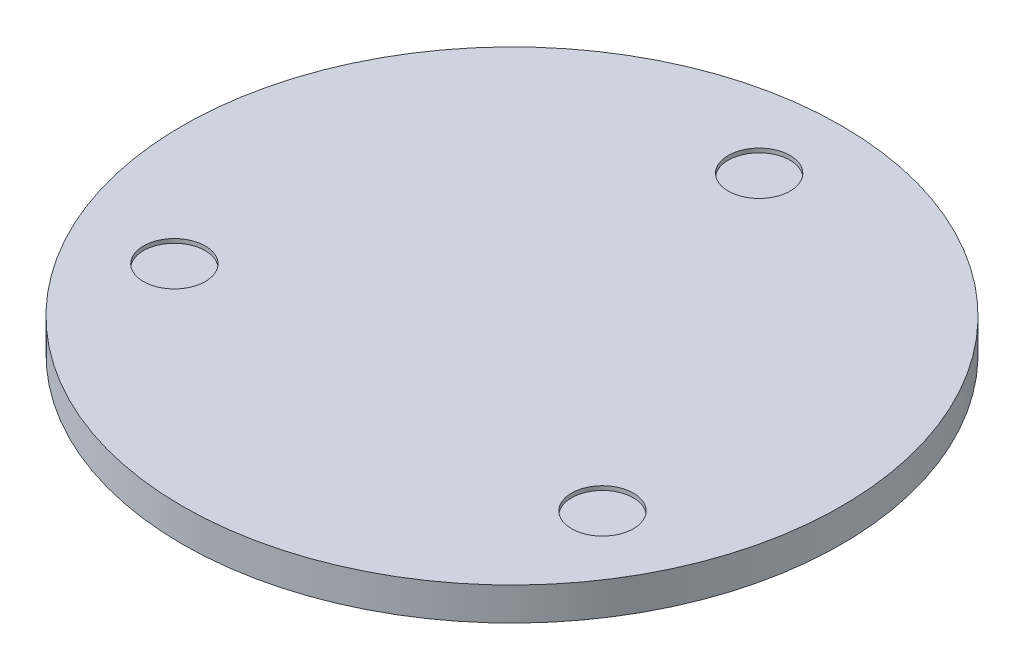
SolidWorks part; units mm, degrees
ref_plane "Front Plane" through (0, 0, 0) normal (0, 0, 1) x (1, 0, 0)
ref_plane "Top Plane" through (0, 0, 0) normal (0, 1, 0) x (1, 0, 0)
ref_plane "Right Plane" through (0, 0, 0) normal (1, 0, 0) x (0, 0, -1)
sketch "Sketch1" plane through (0, 0, 0) normal (0, 0, 1) x (1, 0, 0)
  line L0 (0, 0) -> (-50.8, 0)
  line L1 (-50.8, 0) -> (-50.8, -5.08)
  line L2 (-50.8, -5.08) -> (-38.1, -5.08)
  line L3 (-38.1, -5.08) -> (-38.1, -2.54)
  line L4 (-38.1, -2.54) -> (0, -2.54)
  line L5 (0, -2.54) -> (0, 0)
  dimension "D1" = 50.8
  dimension "D2" = 12.7
  dimension "D3" = 5.08
  dimension "D4" = 2.54
sketch "Sketch2" plane through (0, 0, 0) normal (0, 0, 1) x (1, 0, 0)
  line L0 (0, 4.5677) -> (0, -8.0056) construction
revolve "Revolve1" add sketch "Sketch1" angle 360 about L0
sketch "Sketch3" plane through (0, 0, 0) normal (0, 1, 0) x (1, 0, 0)
  line L0 (0, 0) -> (0, 38.1) construction
  line L1 (0, 0) -> (-32.9956, -19.05) construction
  line L2 (0, 0) -> (32.9956, -19.05) construction
  line L4 (-1.8331, 41.275) -> (-3.6662, 38.1)
  line L5 (-3.6662, 38.1) -> (-1.8331, 34.925)
  line L6 (-1.8331, 34.925) -> (1.8331, 34.925)
  line L7 (1.8331, 34.925) -> (3.6662, 38.1)
  line L8 (3.6662, 38.1) -> (1.8331, 41.275)
  line L9 (1.8331, 41.275) -> (-1.8331, 41.275)
  line L10 (-34.8287, -15.875) -> (-36.6617, -19.05)
  line L11 (-36.6617, -19.05) -> (-34.8287, -22.225)
  line L12 (-34.8287, -22.225) -> (-31.1625, -22.225)
  line L13 (-31.1625, -22.225) -> (-29.3294, -19.05)
  line L14 (-29.3294, -19.05) -> (-31.1625, -15.875)
  line L15 (-31.1625, -15.875) -> (-34.8287, -15.875)
  line L16 (34.8287, -15.875) -> (31.1625, -15.875)
  line L17 (31.1625, -15.875) -> (29.3294, -19.05)
  line L18 (29.3294, -19.05) -> (31.1625, -22.225)
  line L19 (31.1625, -22.225) -> (34.8287, -22.225)
  line L20 (34.8287, -22.225) -> (36.6617, -19.05)
  line L21 (36.6617, -19.05) -> (34.8287, -15.875)
  circle A0 centre (0, 38.1) radius 3.175 construction
  circle A1 centre (-32.9956, -19.05) radius 3.175 construction
  circle A2 centre (0, 38.1) radius 3.175 construction
  circle A3 centre (32.9956, -19.05) radius 3.175 construction
  circle A4 centre (-32.9956, -19.05) radius 3.175 construction
  circle A5 centre (32.9956, -19.05) radius 3.175 construction
  dimension "D2" = 38.1
  dimension "D3" = 120
  dimension "D1" = 6.35
  dimension "D4" = 120
extrude "Cut-Extrude1" cut sketch "Sketch3" against normal blind 0.635
sketch "Sketch4" plane through (0, 0, 0) normal (0, 1, 0) x (1, 0, 0)
  line L0 (-1.8331, 34.925) -> (1.8331, 41.275) construction
  line L1 (-34.8287, -22.225) -> (-31.1625, -15.875) construction
  line L2 (31.1625, -15.875) -> (34.8287, -22.225) construction
  line L3 (31.1625, -22.225) -> (34.8287, -22.225) construction
  circle A0 centre (32.9956, -19.05) radius 4.7625
  circle A1 centre (-32.9956, -19.05) radius 4.7625
  circle A2 centre (0, 38.1) radius 4.7625
  dimension "D1" = 9.525
extrude "Cut-Extrude2" cut sketch "Sketch4" against normal blind 0.635
ref_point "Point1"
